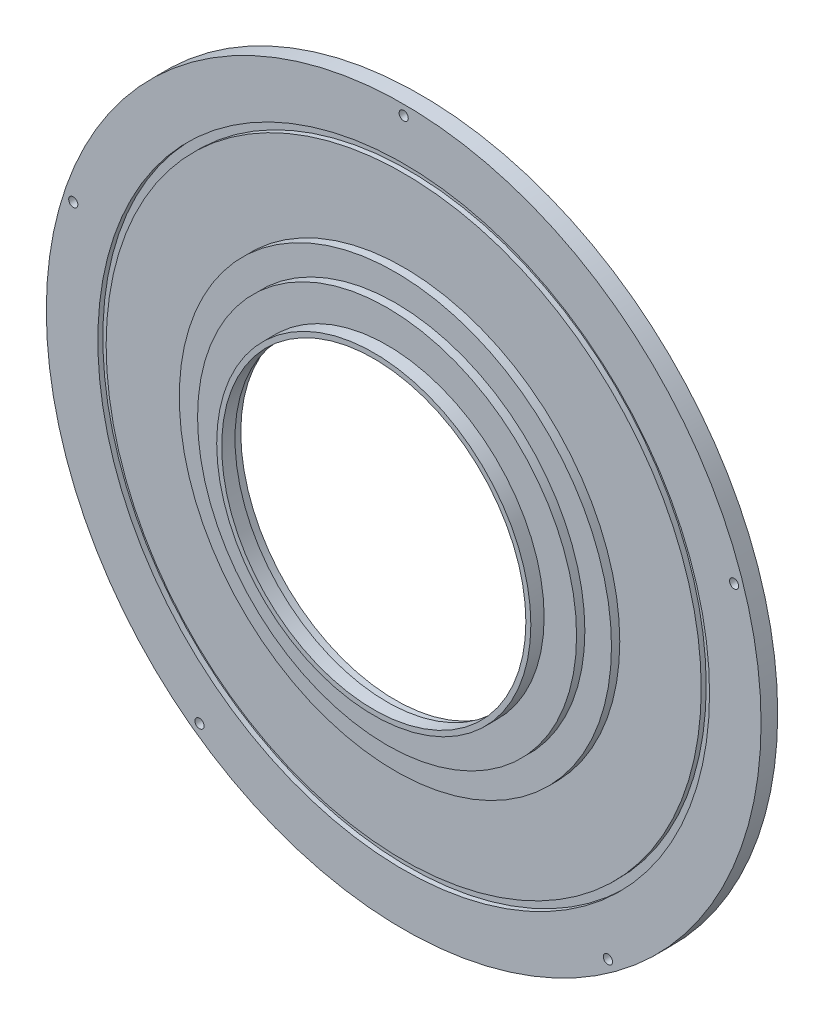
SolidWorks part; units mm, degrees
ref_plane "Front Plane" through (0, 0, 0) normal (0, 0, 1) x (1, 0, 0)
ref_plane "Top Plane" through (0, 0, 0) normal (0, 1, 0) x (1, 0, 0)
ref_plane "Right Plane" through (0, 0, 0) normal (1, 0, 0) x (0, 0, -1)
sketch "Sketch1" plane through (0, 0, 0) normal (0, 0, 1) x (1, 0, 0)
  circle A0 centre (0, 0) radius 215
  circle A1 centre (0, 0) radius 120
extrude "Plate" add sketch "Sketch1" along normal blind 10
ref_plane "Plane_z10" through (0, 0, 10) normal (0, 0, 1) x (1, 0, 0)
sketch "Sketch2" plane through (0, 0, 10) normal (0, 0, 1) x (1, 0, 0)
  circle A0 centre (0, 0) radius 130
  circle A1 centre (0, 0) radius 111
extrude "Bellmouth1" add sketch "Sketch2" along normal blind 5
ref_plane "Plane_z15" through (0, 0, 15) normal (0, 0, 1) x (1, 0, 0)
sketch "Sketch3" plane through (0, 0, 15) normal (0, 0, 1) x (1, 0, 0)
  circle A0 centre (0, 0) radius 114
  circle A1 centre (0, 0) radius 93
extrude "Bellmouth2" add sketch "Sketch3" along normal blind 5
ref_plane "Plane_z20" through (0, 0, 20) normal (0, 0, 1) x (1, 0, 0)
sketch "Sketch4" plane through (0, 0, 20) normal (0, 0, 1) x (1, 0, 0)
  circle A0 centre (0, 0) radius 94.5
  circle A1 centre (0, 0) radius 91.5
extrude "Bellmouth3" add sketch "Sketch4" along normal blind 8
sketch "Sketch5" plane through (0, 0, 0) normal (0, 0, 1) x (1, 0, 0)
  circle A0 centre (0, 0) radius 204
  circle A1 centre (0, 0) radius 144
extrude "Comb_groove" cut sketch "Sketch5" along normal blind 4
ref_plane "Plane_z7" through (0, 0, 7) normal (0, 0, 1) x (1, 0, 0)
sketch "Sketch6" plane through (0, 0, 7) normal (0, 0, 1) x (1, 0, 0)
  circle A0 centre (0, 0) radius 184
  circle A1 centre (0, 0) radius 179
extrude "Band_seat" cut sketch "Sketch6" along normal blind 3
sketch "Sketch7" plane through (0, 0, 0) normal (0, 0, 1) x (1, 0, 0)
  circle A0 centre (198.7708, 64.5846) radius 2.75
  circle A1 centre (0, 209) radius 2.75
  circle A2 centre (-198.7708, 64.5846) radius 2.75
  circle A3 centre (-122.8471, -169.0846) radius 2.75
  circle A4 centre (122.8471, -169.0846) radius 2.75
extrude "Rod_holes" cut sketch "Sketch7" along normal blind 10
